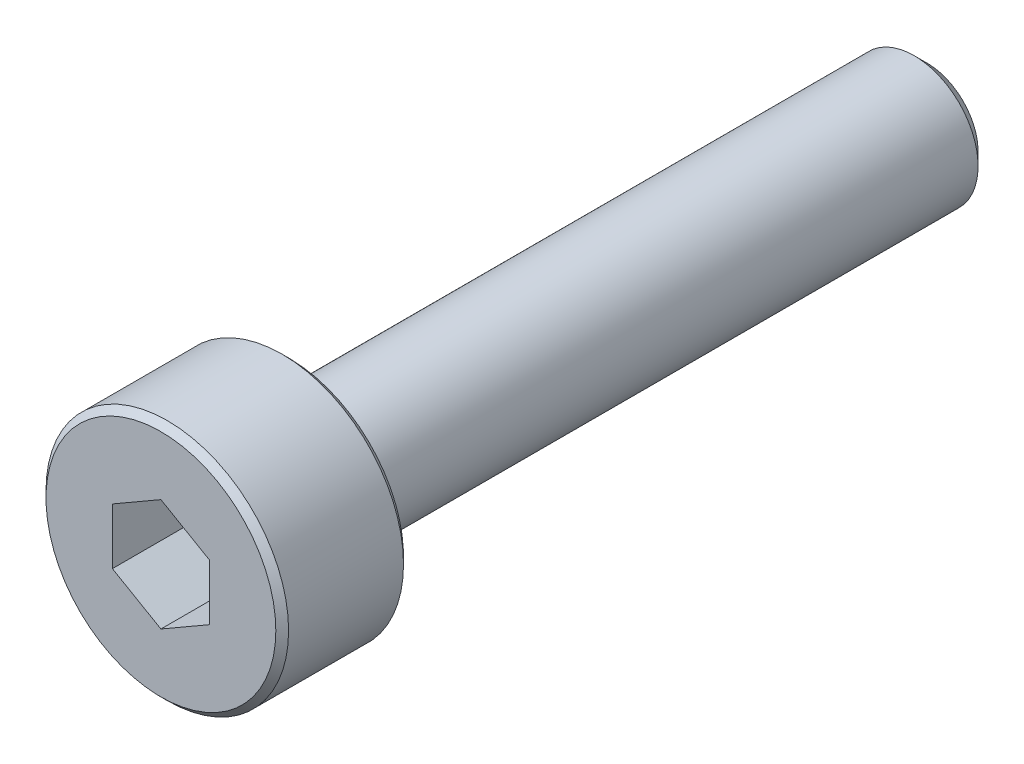
SolidWorks part; units mm, degrees
ref_plane "前视基准面" through (0, 0, 0) normal (0, 0, 1) x (1, 0, 0)
ref_plane "上视基准面" through (0, 0, 0) normal (0, 1, 0) x (1, 0, 0)
ref_plane "右视基准面" through (0, 0, 0) normal (1, 0, 0) x (0, 0, -1)
other "Configuration Table"
sketch "草图1" plane through (0, 0, 0) normal (0, 1, 0) x (1, 0, 0)
  line L0 (1.9, -10) -> (0, -10)
  line L1 (0, -10) -> (0, -12)
  line L2 (0, -12) -> (1.9, -12)
  line L3 (1.9, -12) -> (1.9, -10)
  line L4 (0, -10) -> (0, -12) construction
revolve "旋转1" add sketch "草图1" angle 360 about L4
sketch "草图2" plane through (0, 0, 10) normal (0, 0, -1) x (-1, 0, 0)
  circle A0 centre (0, 0) radius 1
extrude "凸台-拉伸1" add sketch "草图2" along normal blind 10
sketch "草图3" plane through (0, 0, 12) normal (0, 0, 1) x (1, 0, 0)
  line L0 (-0.76, -0.4388) -> (0, -0.8776)
  line L1 (0, -0.8776) -> (0.76, -0.4388)
  line L2 (0.76, -0.4388) -> (0.76, 0.4388)
  line L3 (0.76, 0.4388) -> (0, 0.8776)
  line L4 (0, 0.8776) -> (-0.76, 0.4388)
  line L5 (-0.76, 0.4388) -> (-0.76, -0.4388)
extrude "切除-拉伸1" cut sketch "草图3" against normal blind 1.5
chamfer "倒角1" distance 0.1 angle 45 2 edges at (1.9, 0, 10) (1.9, 0, 12)
chamfer "倒角2" distance 0.2 angle 45 1 edges at (-1, 0, 0)
